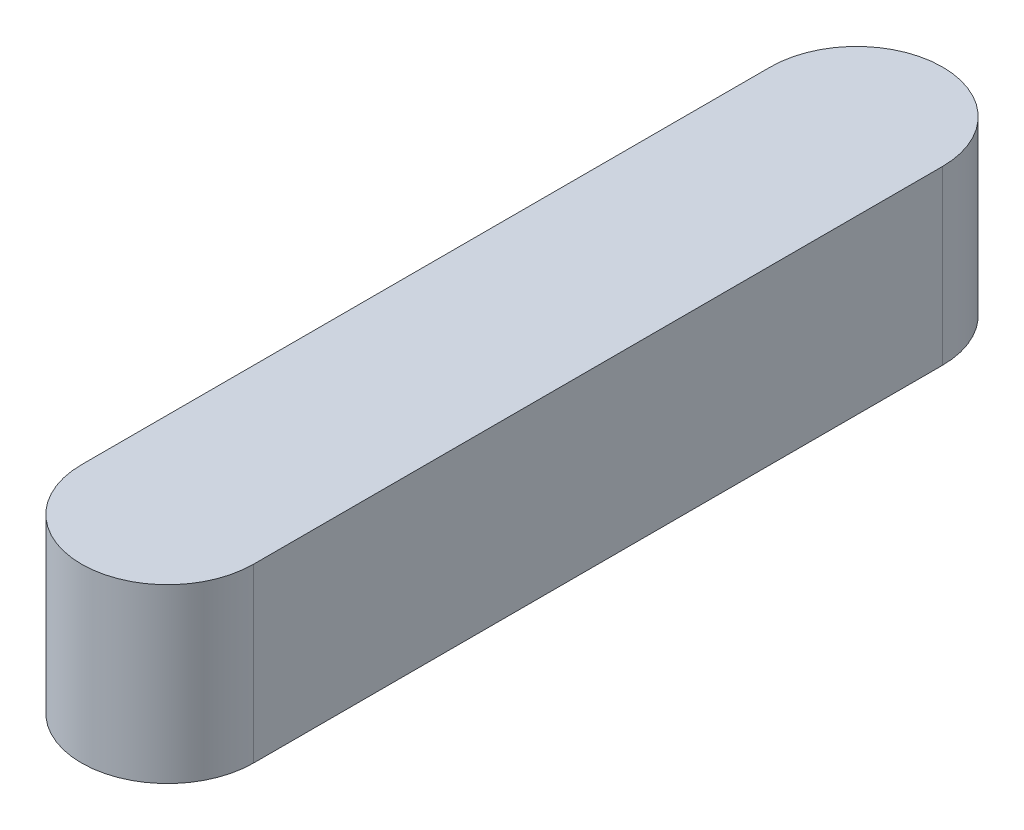
SolidWorks part; units mm, degrees
material "AISI 316 Annealed Stainless Steel Bar (SS)"
ref_plane "Front Plane" through (0, 0, 0) normal (0, 0, 1) x (1, 0, 0)
ref_plane "Top Plane" through (0, 0, 0) normal (0, 1, 0) x (1, 0, 0)
ref_plane "Right Plane" through (0, 0, 0) normal (1, 0, 0) x (0, 0, -1)
sketch "Sketch1" plane through (0, 0, 0) normal (1, 0, 0) x (0, 0, -1)
  line L0 (-10, 2) -> (-10, -2) construction
  line L1 (-10, 2) -> (10, 2) construction
  line L3 (0, 3.85) -> (0, -3.85) construction
  line L4 (4.4, 0) -> (-4.4, 0) construction
  point P0 (-10, 0)
  point P4 (0, 2)
  dimension "Height" = 4
  dimension "Length" = 20
sketch "Sketch3" plane through (0, 0, 0) normal (0, 1, 0) x (1, 0, 0)
  line L0 (0, -8) -> (0, 8) construction
  line L1 (-2, -8) -> (-2, 8)
  line L2 (2, -8) -> (2, 8)
  line L3 (-3.85, 0) -> (3.85, 0) construction
  arc A0 (-2, -8) -> (2, -8) centre (0, -8) ccw
  arc A1 (2, 8) -> (-2, 8) centre (0, 8) ccw
  point P3 (0, 0)
  point P8 (-2, 6)
  point P12 (2, -6)
  dimension "Width" = 4
  dimension "D1" = 4
  dimension "D2" = 4
sketch "Sketch4" plane through (0, 0, 0) normal (0, 1, 0) x (1, 0, 0)
  line L0 (-2, -8) -> (-2, 8) construction
  line L1 (2, -8) -> (2, 8) construction
  line L2 (-2, -8) -> (-2, 8)
  line L3 (2, -8) -> (2, 8)
  arc A0 (2, 8) -> (-2, 8) centre (0, 8) ccw construction
  arc A1 (-2, -8) -> (2, -8) centre (0, -8) ccw construction
  arc A2 (2, 8) -> (-2, 8) centre (0, 8) ccw
  arc A3 (-2, -8) -> (2, -8) centre (0, -8) ccw
extrude "Boss-Extrude1" add sketch "Sketch4" against normal up to vertex (2 mm away) from vertex at 2 starting at point (0, 2, 10)
equation "\"D1@Sketch3\"=\"Width@Sketch3\""
equation "\"D2@Sketch3\"=\"D1@Sketch3\""
